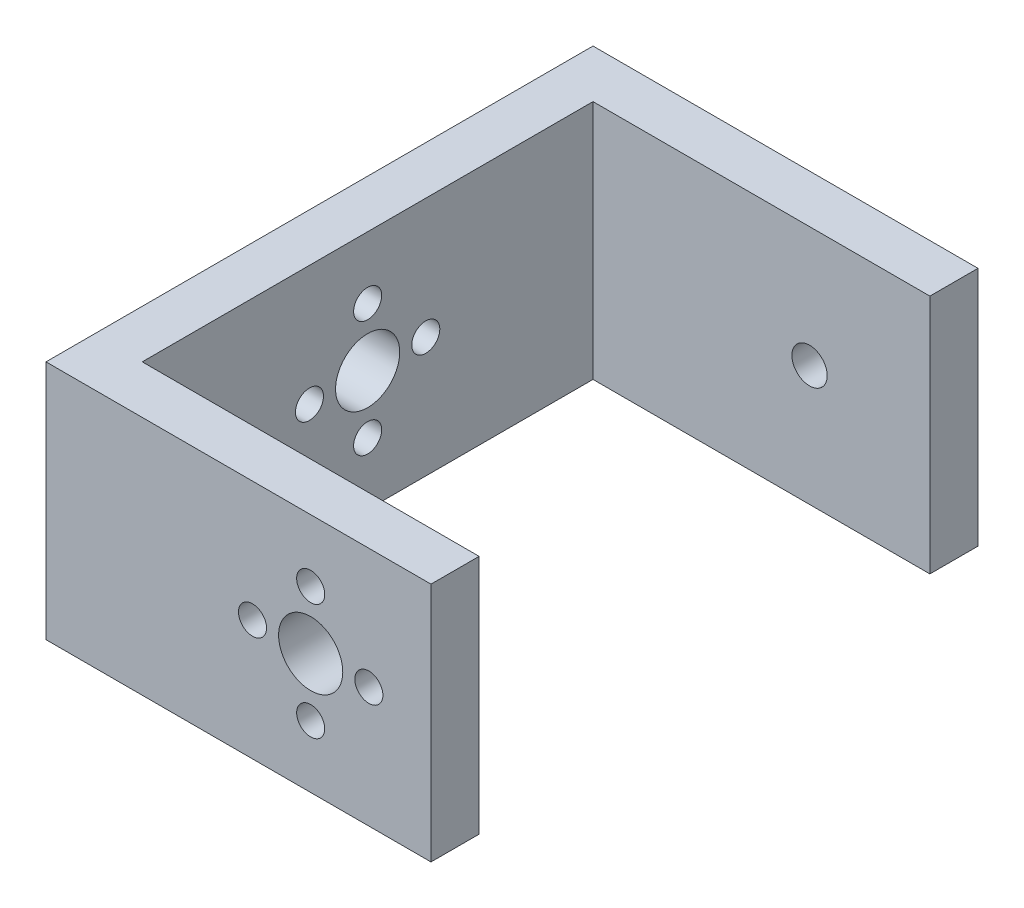
SolidWorks part; units mm, degrees
ref_plane "Front Plane" through (0, 0, 0) normal (0, 0, 1) x (1, 0, 0)
ref_plane "Top Plane" through (0, 0, 0) normal (0, 1, 0) x (1, 0, 0)
ref_plane "Right Plane" through (0, 0, 0) normal (1, 0, 0) x (0, 0, -1)
sketch "Sketch1" plane through (0, 0, 0) normal (0, 1, 0) x (1, 0, 0)
  line L0 (-27, -34.1) -> (21, -34.1)
  line L1 (-21, -28.1) -> (21, -28.1)
  line L2 (-21, -28.1) -> (-21, 28.1)
  line L3 (-21, 28.1) -> (21, 28.1)
  line L4 (21, -28.1) -> (21, 28.1)
  line L5 (-21, -28.1) -> (21, 28.1) construction
  line L6 (-21, 28.1) -> (21, -28.1) construction
  line L7 (-27, -34.1) -> (-27, 34.1)
  line L8 (-27, 34.1) -> (21, 34.1)
  line L9 (21, 34.1) -> (21, 28.1)
  line L10 (21, -28.1) -> (21, -34.1)
  point P0 (0, 0)
  dimension "D1" = 42
  dimension "D2" = 56.2
  dimension "D3" = 6
extrude "Boss-Extrude1" add sketch "Sketch1" along normal blind 30 contours L10 L1 L2 L3 L9 L8 L7 L0
sketch "Sketch2" plane through (-21, 0, 0) normal (1, 0, 0) x (0, 0, -1)
  circle A0 centre (0, 15) radius 4
  circle A1 centre (0, 22.25) radius 1.75
  circle A2 centre (7.25, 15) radius 1.75
  circle A3 centre (0, 7.75) radius 1.75
  circle A4 centre (-7.25, 15) radius 1.75
  point P13 (0, 15)
  dimension "D1" = 8
  dimension "D2" = 3.5
  dimension "D3" = 7.25
  dimension "D5" = 15
  dimension "D4" = 4
extrude "Cut-Extrude1" cut sketch "Sketch2" against normal up to next
sketch "Sketch3" plane through (0, 0, 34.1) normal (0, 0, 1) x (1, 0, 0)
  line L0 (-27, 30) -> (-27, 0) construction
  line L1 (-27, 30) -> (21, 30) construction
  circle A0 centre (6, 15) radius 4
  dimension "D1" = 8
  dimension "D2" = 33
  dimension "D3" = 15
extrude "Cut-Extrude2" cut sketch "Sketch3" against normal up to next
sketch "Sketch4" plane through (0, 0, 34.1) normal (0, 0, 1) x (1, 0, 0)
  circle A0 centre (6, 22.25) radius 1.75
  circle A1 centre (13.25, 15) radius 1.75
  circle A2 centre (6, 7.75) radius 1.75
  circle A3 centre (-1.25, 15) radius 1.75
  point P2 (6, 15)
  point P13 (6, 15)
  dimension "D1" = 3.5
  dimension "D2" = 7.25
  dimension "D3" = 4
extrude "Cut-Extrude3" cut sketch "Sketch4" against normal up to next
sketch "Sketch5" plane through (0, 0, -34.1) normal (0, 0, -1) x (-1, 0, 0)
  circle A0 centre (-6, 15) radius 4 construction
  circle A1 centre (-6, 15) radius 4
  circle A2 centre (-6, 15) radius 2.2
  dimension "D1" = 4.4
extrude "Cut-Extrude4" cut sketch "Sketch5" against normal up to next and the other way through all contours A2
